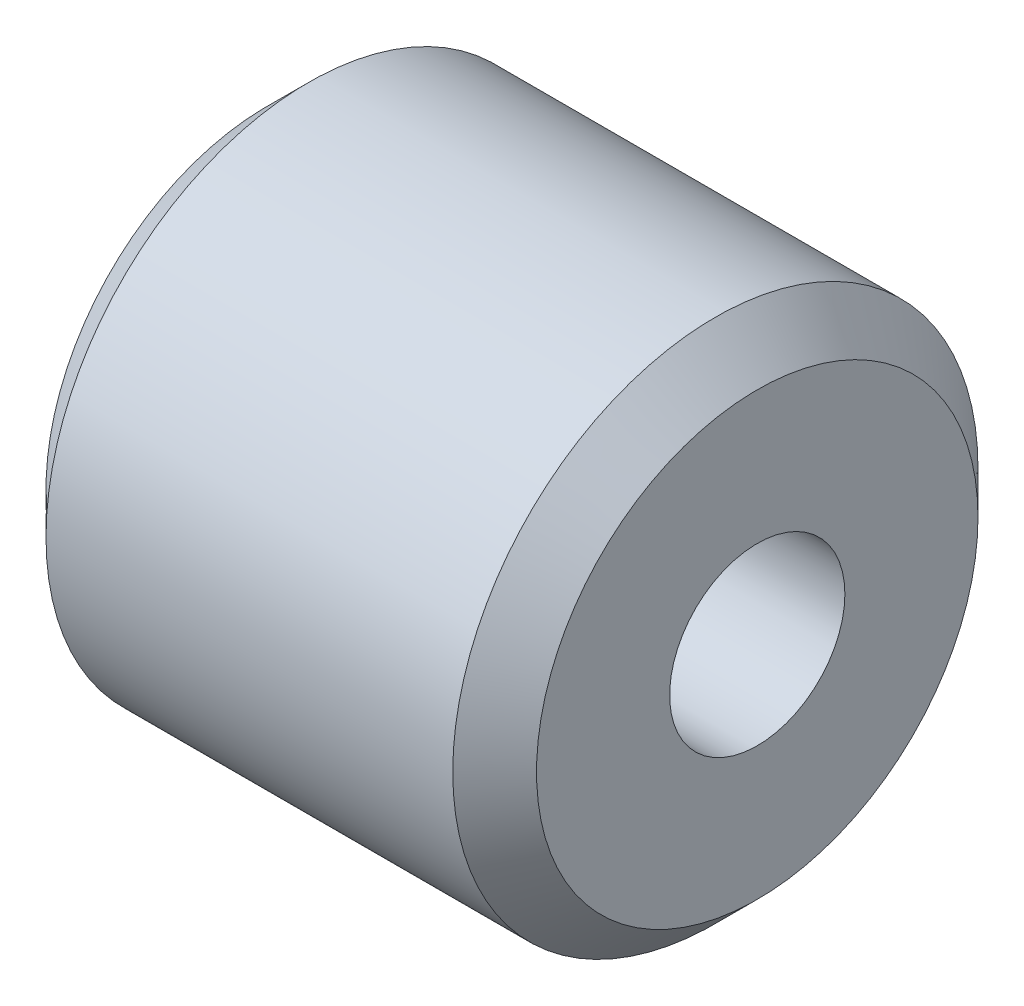
SolidWorks part; units mm, degrees
ref_plane "Front Plane" through (0, 0, 0) normal (0, 0, 1) x (1, 0, 0)
ref_plane "Top Plane" through (0, 0, 0) normal (0, 1, 0) x (1, 0, 0)
ref_plane "Right Plane" through (0, 0, 0) normal (1, 0, 0) x (0, 0, -1)
sketch "Sketch2" plane through (0, 0, 0) normal (1, 0, 0) x (0, 0, -1)
  circle A0 centre (0, 0) radius 1.59
  circle A1 centre (0, 0) radius 4.765
  dimension "D1" = 3.18
  dimension "D2" = 9.53
extrude "Boss-Extrude1" add sketch "Sketch2" along normal mid plane 8.9
chamfer "Chamfer1" distance 0.76 angle 45 2 edges at (-4.45, 0, -4.765) (4.45, 0, -4.765)
